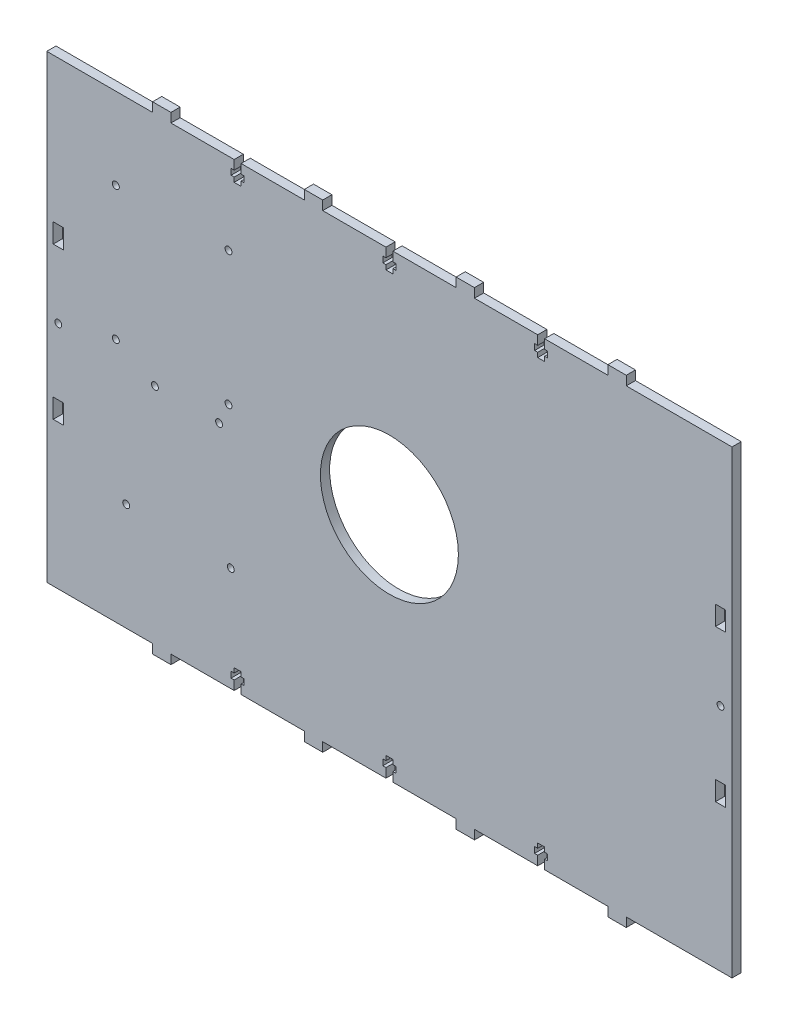
SolidWorks part; units mm, degrees
ref_plane "前视基准面" through (0, 0, 0) normal (0, 0, 1) x (1, 0, 0)
ref_plane "上视基准面" through (0, 0, 0) normal (0, 1, 0) x (1, 0, 0)
ref_plane "右视基准面" through (0, 0, 0) normal (1, 0, 0) x (0, 0, -1)
sketch "草图1" plane through (0, 0, 0) normal (0, 0, 1) x (1, 0, 0)
  line L0 (0, 0) -> (0, -4)
  line L1 (0, -4) -> (-1.35, -4)
  line L2 (-1.35, -4) -> (-1.35, -6.6)
  line L3 (-1.35, -6.6) -> (0, -6.6)
  line L4 (0, -6.6) -> (0, -8.6)
  line L5 (0, -8.6) -> (3, -8.6)
  line L6 (3, -8.6) -> (3, -6.6)
  line L7 (3, -6.6) -> (4.35, -6.6)
  line L8 (4.35, -6.6) -> (4.35, -4)
  line L9 (4.35, -4) -> (3, -4)
  line L10 (3, -4) -> (3, 0)
  line L11 (0, 0) -> (-27.5, 0)
  line L12 (-27.5, 0) -> (-27.5, 4)
  line L13 (-27.5, 4) -> (-35.5, 4)
  line L14 (-35.5, 4) -> (-35.5, 0)
  line L15 (1.5, -8.6) -> (1.5, -56.6) construction
  line L16 (-31.5, 4) -> (-31.5, 0) construction
  line L17 (-67.35, -4) -> (-66, -4)
  line L18 (-66, -6.6) -> (-67.35, -6.6)
  line L19 (-61.65, -6.6) -> (-63, -6.6)
  line L20 (-63, -4) -> (-61.65, -4)
  line L21 (-66, -4) -> (-66, 0)
  line L22 (-66, -8.6) -> (-66, -6.6)
  line L23 (-63, -8.6) -> (-66, -8.6)
  line L24 (-63, -6.6) -> (-63, -8.6)
  line L25 (-67.35, -6.6) -> (-67.35, -4)
  line L26 (-61.65, -4) -> (-61.65, -6.6)
  line L27 (-63, 0) -> (-63, -4)
  line L28 (-63, 0) -> (-35.5, 0)
  line L29 (30.5, 4) -> (38.5, 4)
  line L30 (30.5, 0) -> (30.5, 4)
  line L31 (38.5, 4) -> (38.5, 0)
  line L32 (3, 0) -> (30.5, 0)
  line L33 (66, 0) -> (38.5, 0)
  line L34 (66, 0) -> (66, -4)
  line L35 (64.65, -4) -> (64.65, -6.6)
  line L36 (70.35, -6.6) -> (70.35, -4)
  line L37 (66, -6.6) -> (66, -8.6)
  line L38 (66, -8.6) -> (69, -8.6)
  line L39 (69, -8.6) -> (69, -6.6)
  line L40 (69, -4) -> (69, 0)
  line L41 (66, -4) -> (64.65, -4)
  line L42 (64.65, -6.6) -> (66, -6.6)
  line L43 (69, -6.6) -> (70.35, -6.6)
  line L44 (70.35, -4) -> (69, -4)
  line L45 (67.5, -8.6) -> (67.5, -6.6) construction
  line L46 (69, 0) -> (96.5, 0)
  line L47 (132, 0) -> (104.5, 0)
  line L48 (96.5, 4) -> (96.5, 0)
  line L49 (104.5, 0) -> (104.5, 4)
  line L50 (104.5, 4) -> (96.5, 4)
  line L51 (-64.5, -8.6) -> (-64.5, -6.6) construction
  line L52 (-97.5, 4) -> (-97.5, 0) construction
  line L53 (-66, 0) -> (-93.5, 0)
  line L54 (-93.5, 4) -> (-93.5, 0)
  line L55 (-101.5, 4) -> (-93.5, 4)
  line L56 (-101.5, 0) -> (-101.5, 4)
  line L57 (-129, 0) -> (-101.5, 0)
  line L58 (1.5, -8.6) -> (-140.5, -8.6) construction
  line L59 (-129, 0) -> (-140.5, 0)
  line L60 (132, 0) -> (143.5, 0)
  line L64 (-140.5, 0) -> (-142.5, 0)
  line L65 (-129, -200) -> (-140.5, -200)
  line L66 (1.5, -141.4) -> (1.5, -143.4) construction
  line L67 (3, -196) -> (3, -200)
  line L68 (4.35, -196) -> (3, -196)
  line L69 (4.35, -193.4) -> (4.35, -196)
  line L70 (3, -193.4) -> (4.35, -193.4)
  line L71 (3, -191.4) -> (3, -193.4)
  line L72 (0, -191.4) -> (3, -191.4)
  line L73 (0, -193.4) -> (0, -191.4)
  line L74 (-1.35, -193.4) -> (0, -193.4)
  line L75 (-1.35, -196) -> (-1.35, -193.4)
  line L76 (0, -196) -> (-1.35, -196)
  line L77 (0, -200) -> (0, -196)
  line L78 (132, -200) -> (143.5, -200)
  line L79 (67.5, -141.4) -> (67.5, -143.4) construction
  line L80 (104.5, -204) -> (96.5, -204)
  line L81 (104.5, -200) -> (104.5, -204)
  line L82 (96.5, -204) -> (96.5, -200)
  line L83 (132, -200) -> (104.5, -200)
  line L84 (69, -200) -> (96.5, -200)
  line L85 (70.35, -196) -> (69, -196)
  line L86 (69, -193.4) -> (70.35, -193.4)
  line L87 (64.65, -193.4) -> (66, -193.4)
  line L88 (66, -196) -> (64.65, -196)
  line L89 (69, -196) -> (69, -200)
  line L90 (69, -191.4) -> (69, -193.4)
  line L91 (66, -191.4) -> (69, -191.4)
  line L92 (66, -193.4) -> (66, -191.4)
  line L93 (70.35, -193.4) -> (70.35, -196)
  line L94 (64.65, -196) -> (64.65, -193.4)
  line L95 (66, -200) -> (66, -196)
  line L96 (66, -200) -> (38.5, -200)
  line L97 (3, -200) -> (30.5, -200)
  line L98 (38.5, -204) -> (38.5, -200)
  line L99 (30.5, -200) -> (30.5, -204)
  line L100 (30.5, -204) -> (38.5, -204)
  line L101 (1.5, -141.4) -> (-140.5, -141.4) construction
  line L102 (-97.5, -154) -> (-97.5, -150) construction
  line L103 (-64.5, -141.4) -> (-64.5, -143.4) construction
  line L104 (-31.5, -154) -> (-31.5, -150) construction
  line L105 (-129, -200) -> (-101.5, -200)
  line L106 (-101.5, -200) -> (-101.5, -204)
  line L107 (-101.5, -204) -> (-93.5, -204)
  line L108 (-93.5, -204) -> (-93.5, -200)
  line L109 (-66, -200) -> (-93.5, -200)
  line L110 (-63, -200) -> (-35.5, -200)
  line L111 (-63, -200) -> (-63, -196)
  line L112 (-61.65, -196) -> (-61.65, -193.4)
  line L113 (-67.35, -193.4) -> (-67.35, -196)
  line L114 (-63, -193.4) -> (-63, -191.4)
  line L115 (-63, -191.4) -> (-66, -191.4)
  line L116 (-66, -191.4) -> (-66, -193.4)
  line L117 (-66, -196) -> (-66, -200)
  line L118 (-63, -196) -> (-61.65, -196)
  line L119 (-61.65, -193.4) -> (-63, -193.4)
  line L120 (-66, -193.4) -> (-67.35, -193.4)
  line L121 (-67.35, -196) -> (-66, -196)
  line L122 (-35.5, -204) -> (-35.5, -200)
  line L123 (-27.5, -204) -> (-35.5, -204)
  line L124 (-27.5, -200) -> (-27.5, -204)
  line L125 (0, -200) -> (-27.5, -200)
  line L137 (-142.5, 0) -> (-142.5, -200) construction
  line L138 (-142.5, -200) -> (-140.5, -200)
  line L140 (-144.7, -62.8) -> (-140.3, -62.8)
  line L141 (-144.7, -62.8) -> (-144.7, -71.2)
  line L142 (-144.7, -71.2) -> (-140.3, -71.2)
  line L143 (-140.3, -62.8) -> (-140.3, -71.2)
  line L144 (-144.7, -62.8) -> (-140.3, -71.2) construction
  line L145 (-144.7, -71.2) -> (-140.3, -62.8) construction
  line L146 (-142.5, -100) -> (-134.9383, -100) construction
  line L148 (-140.3, -137.2) -> (-140.3, -128.8)
  line L149 (-144.7, -137.2) -> (-144.7, -128.8)
  line L150 (-144.7, -128.8) -> (-140.3, -128.8)
  line L151 (-144.7, -137.2) -> (-140.3, -137.2)
  line L152 (-142.5, 0) -> (-147.5, 0)
  line L153 (-147.5, 0) -> (-147.5, -200)
  line L154 (-147.5, -200) -> (-142.5, -200)
  line L156 (145.5, -200) -> (143.5, -200)
  line L157 (150.5, -200) -> (145.5, -200)
  line L158 (143.5, 0) -> (145.5, 0)
  line L159 (145.5, 0) -> (150.5, 0)
  line L160 (150.5, 0) -> (150.5, -200)
  line L161 (145.5, -100) -> (137.9383, -100) construction
  line L162 (147.7, -71.2) -> (143.3, -62.8) construction
  line L163 (147.7, -62.8) -> (143.3, -71.2) construction
  line L164 (145.5, 0) -> (145.5, -200) construction
  line L165 (147.7, -137.2) -> (143.3, -137.2)
  line L166 (147.7, -128.8) -> (143.3, -128.8)
  line L167 (147.7, -137.2) -> (147.7, -128.8)
  line L168 (143.3, -137.2) -> (143.3, -128.8)
  line L169 (143.3, -62.8) -> (143.3, -71.2)
  line L170 (147.7, -71.2) -> (143.3, -71.2)
  line L171 (147.7, -62.8) -> (147.7, -71.2)
  line L172 (147.7, -62.8) -> (143.3, -62.8)
  circle A0 centre (-142.5, -100) radius 1.5
  circle A1 centre (145.5, -100) radius 1.5
  circle A2 centre (1.5, -100) radius 30
  point P139 (-142.5, -67)
  point P166 (145.5, -67)
  dimension "D9" = 33
  dimension "D1" = 3
  dimension "D2" = 2
  dimension "D3" = 4
  dimension "D4" = 2.6
  dimension "D5" = 1.35
  dimension "D6" = 200
  dimension "D7" = 4
  dimension "D8" = 284
  dimension "D10" = 4.4
  dimension "D11" = 2
  dimension "D12" = 8.4
  dimension "D13" = 5
extrude "凸台-拉伸1" add sketch "草图1" along normal blind 4
sketch "草图2" plane through (0, 0, 0) normal (0, 1, 0) x (1, 0, 0)
  line L0 (0, -2) -> (3, -2)
  line L1 (0, -4) -> (0, 0) construction
  line L2 (3, -4) -> (3, 0) construction
  circle A0 centre (1.5, -2) radius 1.5
sketch "草图3" plane through (0, -200, 0) normal (0, -1, 0) x (1, 0, 0)
  line L0 (0, 2) -> (3, 2)
  line L1 (0, 4) -> (0, 0) construction
  line L2 (3, 4) -> (3, 0) construction
  circle A0 centre (1.5, 2) radius 1.5
sketch "草图4" plane through (0, 0, 4) normal (0, 0, 1) x (1, 0, 0)
  line L0 (-118.2649, -100.0242) -> (-64.9649, -100.0242) construction
  line L1 (-118.2649, -100.0242) -> (-118.2649, -168.6242) construction
  line L2 (-118.2649, -168.6242) -> (-64.9649, -168.6242) construction
  line L3 (-64.9649, -100.0242) -> (-64.9649, -168.6242) construction
  line L4 (-117.4649, -35.442) -> (-117.4649, -93.442) construction
  line L5 (-117.4649, -35.442) -> (-68.4649, -35.442) construction
  line L6 (-68.4649, -35.442) -> (-68.4649, -93.442) construction
  line L7 (-117.4649, -93.442) -> (-120.9649, -93.442)
  line L8 (-120.9649, -11.942) -> (-64.9649, -11.942) construction
  line L9 (-120.9649, -11.942) -> (-120.9649, -96.942) construction
  line L10 (-120.9649, -96.942) -> (-64.9649, -96.942) construction
  line L11 (-64.9649, -11.942) -> (-64.9649, -96.942) construction
  line L12 (-68.4649, -93.442) -> (-64.9649, -93.442) construction
  circle A0 centre (-100.4649, -102.5242) radius 1.5
  circle A1 centre (-72.5649, -102.5242) radius 1.5
  circle A2 centre (-112.9649, -153.3242) radius 1.5
  circle A3 centre (-67.4649, -154.6242) radius 1.5
  circle A4 centre (-117.4649, -35.442) radius 1.5
  circle A5 centre (-68.4649, -35.442) radius 1.5
  circle A6 centre (-117.4649, -93.442) radius 1.5
  circle A7 centre (-68.4649, -93.442) radius 1.5
  dimension "D1" = 3
  dimension "D2" = 58
  dimension "D3" = 49
  dimension "D4" = 85
  dimension "D5" = 56
  dimension "D6" = 3.5
extrude "切除-拉伸1" cut sketch "草图4" against normal blind 10
